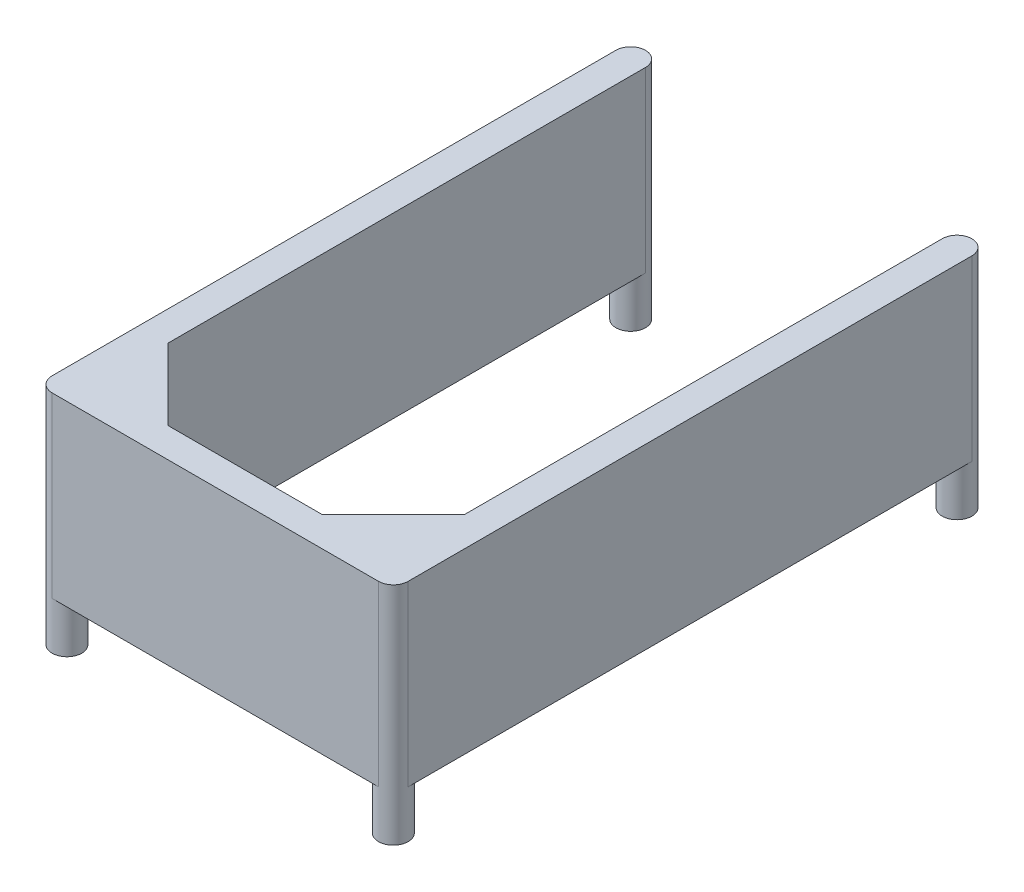
SolidWorks part; units mm, degrees
ref_plane "Front Plane" through (0, 0, 0) normal (0, 0, 1) x (1, 0, 0)
ref_plane "Top Plane" through (0, 0, 0) normal (0, 1, 0) x (1, 0, 0)
ref_plane "Right Plane" through (0, 0, 0) normal (1, 0, 0) x (0, 0, -1)
sketch "Sketch1" plane through (0, 0, 0) normal (0, 1, 0) x (1, 0, 0)
  line L0 (0, 0) -> (0, 120.65) construction
  line L1 (-3.175, 0) -> (-3.175, 120.65)
  line L2 (3.175, 3.175) -> (3.175, 120.65)
  line L3 (0, 0) -> (69.85, 0) construction
  line L4 (3.175, 3.175) -> (66.675, 3.175)
  line L5 (0, -3.175) -> (69.85, -3.175)
  line L6 (69.85, 0) -> (69.85, 120.65) construction
  line L7 (66.675, 3.175) -> (66.675, 120.65)
  line L8 (73.025, 0) -> (73.025, 120.65)
  arc A0 (-3.175, 0) -> (0, -3.175) centre (0, 0) ccw
  arc A1 (3.175, 120.65) -> (-3.175, 120.65) centre (0, 120.65) ccw
  arc A3 (69.85, -3.175) -> (73.025, 0) centre (69.85, 0) ccw
  arc A5 (73.025, 120.65) -> (66.675, 120.65) centre (69.85, 120.65) ccw
  point P3 (0, 60.325)
  point P8 (34.925, 0)
  point P15 (69.85, 60.325)
  dimension "D1" = 6.35
  dimension "D2" = 6.35
  dimension "D4" = 69.85
  dimension "D5" = 120.65
  dimension "D6" = 120.65
extrude "Boss-Extrude1" add sketch "Sketch1" along normal blind 38.1
sketch "Sketch2" plane through (0, 0, 0) normal (0, -1, 0) x (-1, 0, 0)
  circle A0 centre (-69.85, 120.65) radius 3.175
  circle A1 centre (0, 120.65) radius 3.175
  circle A2 centre (0, 0) radius 3.175
  circle A3 centre (-69.85, 0) radius 3.175
extrude "Boss-Extrude2" add sketch "Sketch2" along normal blind 10.16
chamfer "Chamfer1" distance 15.24 angle 45 2 edges at (66.675, 19.05, -3.175) (3.175, 19.05, -3.175)
